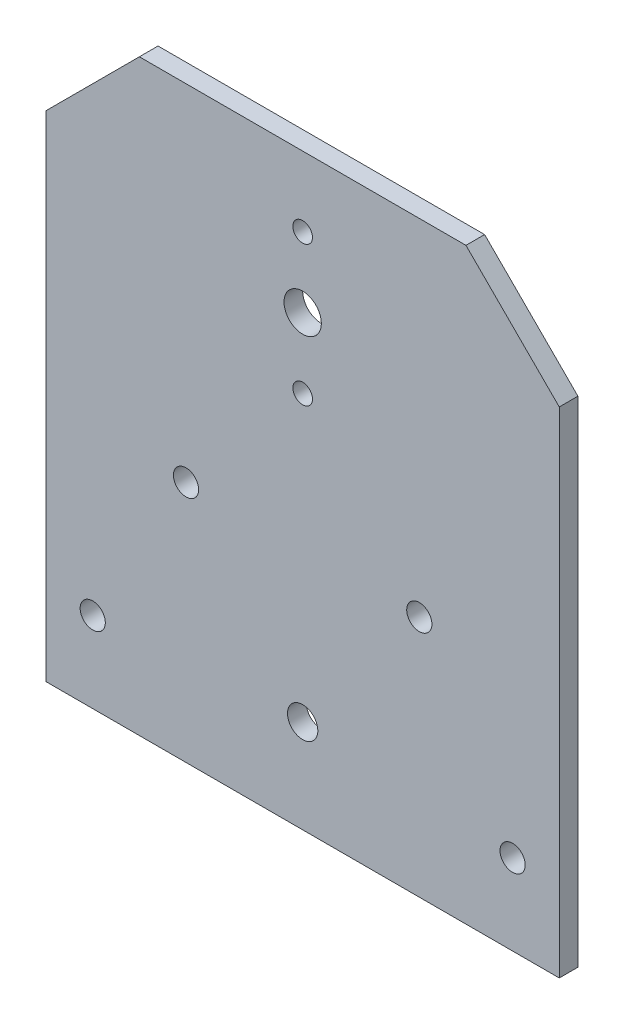
SolidWorks part; units mm, degrees
ref_plane "前视基准面" through (0, 0, 0) normal (0, 0, 1) x (1, 0, 0)
ref_plane "上视基准面" through (0, 0, 0) normal (0, 1, 0) x (1, 0, 0)
ref_plane "右视基准面" through (0, 0, 0) normal (1, 0, 0) x (0, 0, -1)
sketch "草图1" plane through (0, 0, 0) normal (0, 0, 1) x (1, 0, 0)
  line L1 (-67.2661, 25.9722) -> (42.7339, 25.9722)
  line L2 (-67.2661, 25.9722) -> (-67.2661, -100.0278)
  line L3 (-67.2661, -100.0278) -> (42.7339, -100.0278)
  line L4 (42.7339, 25.9722) -> (42.7339, -100.0278)
  dimension "D1" = 110
  dimension "D2" = 126
extrude "凸台-拉伸1" add sketch "草图1" along normal blind 4
sketch "草图2" plane through (0, 0, 4) normal (0, 0, 1) x (1, 0, 0)
  circle A0 centre (12.7339, -48.0278) radius 2.7
  circle A1 centre (32.7339, -82.7278) radius 2.7
  circle A2 centre (-37.2661, -48.0278) radius 2.7
  circle A3 centre (-57.2661, -82.7278) radius 2.7
  circle A4 centre (-12.2661, -80.0278) radius 3.25
  circle A5 centre (-12.2661, -4.0278) radius 4
  circle A7 centre (-12.2661, 10.9722) radius 2.1
  circle A8 centre (-12.2661, -19.0278) radius 2.1
  dimension "D5" = 5.4
  dimension "D6" = 5.4
  dimension "D1" = 5.4
  dimension "D2" = 5.4
  dimension "D4" = 6.5
  dimension "D8" = 8
  dimension "D9" = 4.2
  dimension "D10" = 4.2
extrude "切除-拉伸2" cut sketch "草图2" against normal blind 4
sketch "草图3" plane through (0, 0, 4) normal (0, 0, 1) x (1, 0, 0)
  line L0 (-67.2661, 5.9722) -> (-47.2661, 25.9722)
  line L1 (-67.2661, 25.9722) -> (-67.2661, -100.0278) construction
  line L2 (42.7339, 25.9722) -> (-67.2661, 25.9722) construction
  line L3 (22.7339, 25.9722) -> (42.7339, 5.9722)
  line L4 (42.7339, -100.0278) -> (42.7339, 25.9722) construction
  line L5 (-47.2661, 25.9722) -> (-67.2661, 25.9722)
  line L6 (42.7339, 25.9722) -> (22.7339, 25.9722)
  line L7 (-67.2661, 25.9722) -> (-67.2661, 5.9722)
  line L8 (42.7339, 25.9722) -> (42.7339, 5.9722)
  dimension "D1" = 20
  dimension "D2" = 20
  dimension "D3" = 20
  dimension "D4" = 20
extrude "切除-拉伸3" cut sketch "草图3" against normal blind 4
